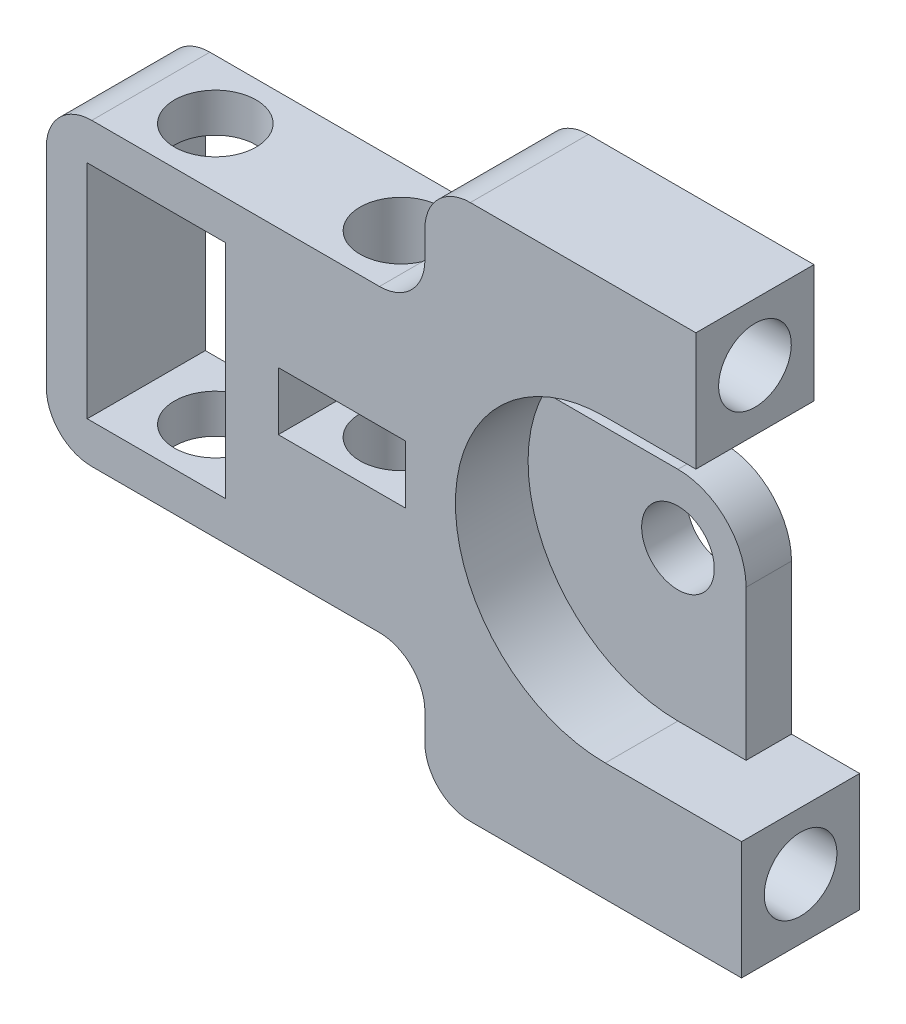
SolidWorks part; units mm, degrees
ref_plane "Alzado" through (0, 0, 0) normal (0, 0, 1) x (1, 0, 0)
ref_plane "Planta" through (0, 0, 0) normal (0, 1, 0) x (1, 0, 0)
ref_plane "Vista lateral" through (0, 0, 0) normal (1, 0, 0) x (0, 0, -1)
sketch "Croquis1" plane through (0, 0, 0) normal (0, 0, 1) x (1, 0, 0)
  line L0 (9.9762, 29.5) -> (9.9762, 16.5)
  line L1 (-49.43, 0) -> (0, 0) construction
  line L2 (9.9762, 29.5) -> (-14.8577, 29.5)
  line L3 (-19.8577, 24.5) -> (-19.8577, 21.5)
  line L4 (15, -29.5) -> (15, -16.5)
  line L5 (9.9762, 16.5) -> (0.0218, 16.5)
  line L6 (15, -16.5) -> (0, -16.5)
  line L7 (-49.43, 16.5) -> (-49.43, -16.5) construction
  line L8 (-29, 16.5) -> (-29, -16.5) construction
  line L9 (-53.43, 16.5) -> (-53.43, -16.5) construction
  line L10 (-33, 16.5) -> (-33, -16.5) construction
  line L11 (-45.43, 16.5) -> (-45.43, -16.5) construction
  line L12 (-25, 16.5) -> (-25, -16.5) construction
  line L13 (-24.8577, 16.5) -> (-56.53, 16.5)
  line L14 (-57.03, -12.2) -> (-41.83, -12.2)
  line L15 (-57.03, -12.2) -> (-57.03, 12.2)
  line L16 (-57.03, 12.2) -> (-41.83, 12.2)
  line L17 (-41.83, -12.2) -> (-41.83, 12.2)
  line L18 (-57.03, -12.2) -> (-41.83, 12.2) construction
  line L19 (-57.03, 12.2) -> (-41.83, -12.2) construction
  line L20 (-36, -3.2) -> (-22, -3.2)
  line L21 (-36, -3.2) -> (-36, 3.2)
  line L22 (-36, 3.2) -> (-22, 3.2)
  line L23 (-22, -3.2) -> (-22, 3.2)
  line L24 (-36, -3.2) -> (-22, 3.2) construction
  line L25 (-36, 3.2) -> (-22, -3.2) construction
  line L26 (-61.53, 11.5) -> (-61.53, -11.5)
  line L27 (-56.53, -16.5) -> (-24.8577, -16.5)
  line L28 (-19.8577, -21.5) -> (-19.8577, -24.5)
  line L29 (-14.8577, -29.5) -> (15, -29.5)
  arc A0 (0.0218, 16.5) -> (0, -16.5) centre (0, 0) ccw
  arc A1 (-14.8577, 29.5) -> (-19.8577, 24.5) centre (-14.8577, 24.5) ccw
  arc A2 (-14.8577, -29.5) -> (-19.8577, -24.5) centre (-14.8577, -24.5) cw
  arc A3 (-56.53, -16.5) -> (-61.53, -11.5) centre (-56.53, -11.5) cw
  arc A4 (-56.53, 16.5) -> (-61.53, 11.5) centre (-56.53, 11.5) ccw
  arc A5 (-19.8577, -21.5) -> (-24.8577, -16.5) centre (-24.8577, -21.5) ccw
  arc A6 (-19.8577, 21.5) -> (-24.8577, 16.5) centre (-24.8577, 21.5) cw
  point P0 (0, 0)
  point P22 (-49.43, 0)
  point P27 (-29, 0)
  dimension "D15" = 16.5
  dimension "D2" = 5
  dimension "D8" = 5
  dimension "D14" = 5
  dimension "D16" = 5
  dimension "D17" = 5
  dimension "D18" = 5
  dimension "D22" = 29
  dimension "D3" = 13
  dimension "D4" = 15
  dimension "D5" = 15
  dimension "D6" = 4
  dimension "D7" = 4
  dimension "D9" = 20.43
  dimension "D10" = 24.4
  dimension "D11" = 15.2
  dimension "D12" = 14
  dimension "D13" = 6.4
  dimension "D19" = 4.5
  dimension "D20" = 29.8577
  dimension "D21" = 24.8339
extrude "Saliente-Extruir2" add sketch "Croquis1" along normal blind 8
sketch "Croquis2" plane through (0, 0, 0) normal (0, 0, -1) x (-1, 0, 0)
  line L0 (24.8577, 16.5) -> (61.5471, 16.5)
  line L1 (61.5471, 16.5) -> (61.5471, -16.5)
  line L2 (61.5471, -16.5) -> (24.8577, -16.5)
  line L3 (19.8577, -21.5) -> (19.8577, -29.5)
  line L4 (19.8577, -29.5) -> (-15, -29.5)
  line L5 (-15, -29.5) -> (-15, -16.5)
  line L6 (-7.5, 0) -> (-7.5, -16.5)
  line L7 (-9.9762, 16.5) -> (-9.9762, 29.5)
  line L8 (-9.9762, 29.5) -> (19.8577, 29.5)
  line L9 (19.8577, 29.5) -> (19.8577, 21.5)
  line L10 (0, 7.5) -> (14.6969, 7.5)
  line L11 (57.03, 12.2) -> (57.03, -12.2) construction
  line L12 (-15, -16.5) -> (0, -16.5) construction
  line L13 (-0.0218, 16.5) -> (-9.9762, 16.5) construction
  line L14 (-0.0218, 16.5) -> (-9.9762, 16.5)
  line L15 (-7.5, -16.5) -> (-15, -16.5)
  arc A0 (19.8577, 21.5) -> (24.8577, 16.5) centre (24.8577, 21.5) ccw construction
  arc A1 (0, -16.5) -> (-0.0218, 16.5) centre (0, 0) ccw construction
  circle A2 centre (0, 0) radius 4
  arc A3 (-7.5, 0) -> (0, 7.5) centre (0, 0) cw
  arc A4 (14.6969, 7.5) -> (-0.0218, 16.5) centre (0, 0) ccw
  arc A5 (19.8577, -21.5) -> (24.8577, -16.5) centre (24.8577, -21.5) cw
  arc A6 (19.8577, 21.5) -> (24.8577, 16.5) centre (24.8577, 21.5) ccw
  arc A8 (24.8577, -16.5) -> (19.8577, -21.5) centre (24.8577, -21.5) ccw construction
  point P34 (19.8577, -16.5)
  point P37 (19.8577, 16.5)
  dimension "D1" = 8
  dimension "D2" = 5
  dimension "D3" = 5
  dimension "D4" = 7.5
  dimension "D5" = 14.6969
  dimension "D6" = 4.5171
extrude "Saliente-Extruir4" add sketch "Croquis2" along normal blind 5
sketch "Croquis3" plane through (9.9762, 0, 0) normal (1, 0, 0) x (0, 0, -1)
  circle A0 centre (-1.5, 23.1516) radius 4
  dimension "D1" = 8
extrude "Cortar-Extruir1" cut sketch "Croquis3" against normal blind 25
sketch "Croquis4" plane through (15, 0, 0) normal (1, 0, 0) x (0, 0, -1)
  circle A0 centre (-1.5, -22.8483) radius 4
  dimension "D1" = 8
extrude "Cortar-Extruir2" cut sketch "Croquis4" against normal blind 30.02
sketch "Croquis5" plane through (0, 16.5, 0) normal (0, 1, 0) x (1, 0, 0)
  line L0 (-24.8577, -8) -> (-56.53, -8) construction
  line L1 (-61.53, -8) -> (-61.53, 5) construction
  circle A0 centre (-49.43, -1.5) radius 4.5
  circle A1 centre (-29, -1.5) radius 4.5
  dimension "D4" = 9
  dimension "D3" = 12.1
  dimension "D1" = 6.5
  dimension "D2" = 20.43
extrude "Cortar-Extruir3" cut sketch "Croquis5" against normal up to surface (33 mm away) up to face at (-40.6938, -16.5, 1.5)
